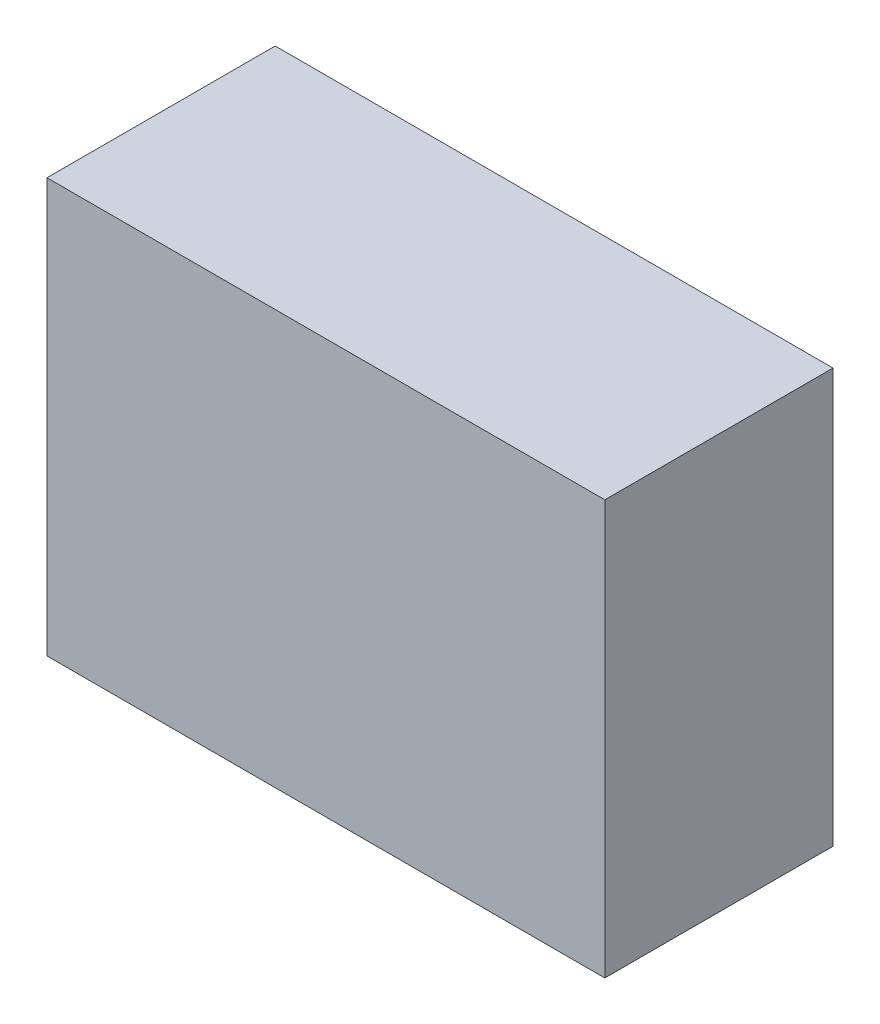
SolidWorks part; units mm, degrees
ref_plane "Front Plane" through (0, 0, 0) normal (0, 0, 1) x (1, 0, 0)
ref_plane "Top Plane" through (0, 0, 0) normal (0, 1, 0) x (1, 0, 0)
ref_plane "Right Plane" through (0, 0, 0) normal (1, 0, 0) x (0, 0, -1)
sketch "Sketch1" plane through (0, 0, 0) normal (0, 0, 1) x (1, 0, 0)
  line L1 (-33, -24.5) -> (33, -24.5)
  line L2 (-33, -24.5) -> (-33, 24.5)
  line L3 (-33, 24.5) -> (33, 24.5)
  line L4 (33, -24.5) -> (33, 24.5)
  line L5 (-33, -24.5) -> (33, 24.5) construction
  line L6 (-33, 24.5) -> (33, -24.5) construction
  point P0 (0, 0)
extrude "Envelope" add sketch "Sketch1" along normal blind 27
